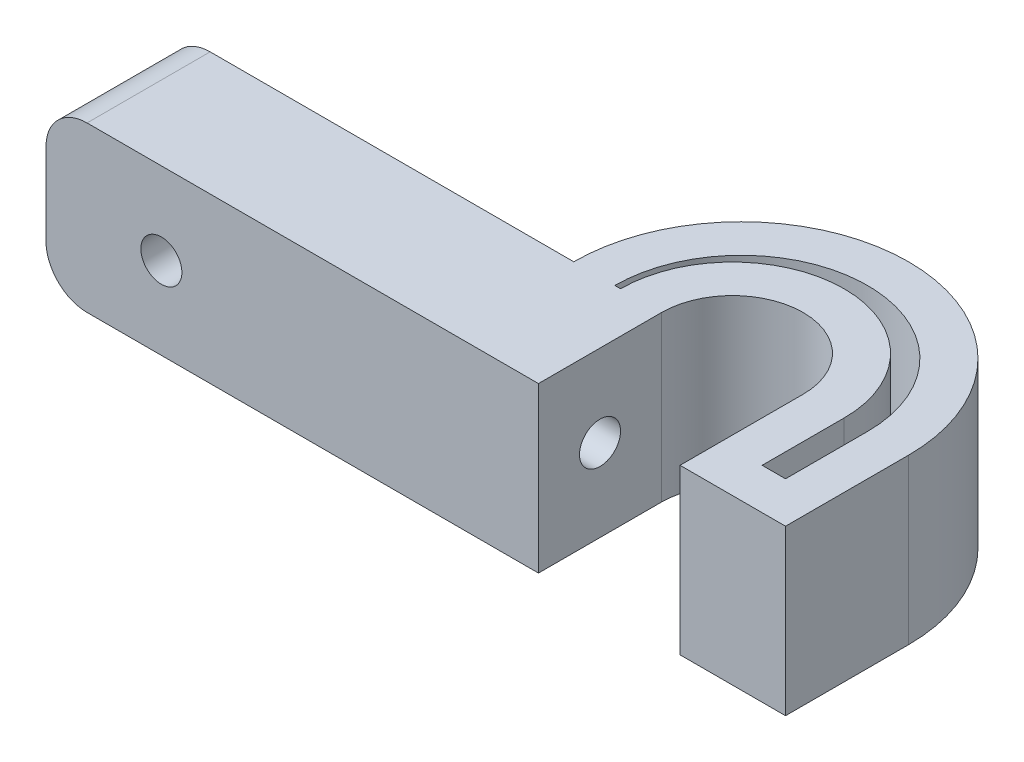
SolidWorks part; units mm, degrees
ref_plane "Plan de face" through (0, 0, 0) normal (0, 0, 1) x (1, 0, 0)
ref_plane "Plan de dessus" through (0, 0, 0) normal (0, 1, 0) x (1, 0, 0)
ref_plane "Plan de droite" through (0, 0, 0) normal (1, 0, 0) x (0, 0, -1)
sketch "Esquisse1" plane through (0, 0, 0) normal (0, 0, 1) x (1, 0, 0)
  line L1 (-50, -20) -> (60, -20)
  line L2 (-60, -10) -> (-60, 10)
  line L3 (-50, 20) -> (60, 20)
  line L4 (60, -20) -> (60, 20)
  line L5 (-60, -20) -> (60, 20) construction
  line L6 (-60, 20) -> (60, -20) construction
  arc A2 (-50, -20) -> (-60, -10) centre (-50, -10) cw
  arc A3 (-60, 10) -> (-50, 20) centre (-50, 10) cw
  point P0 (0, 0)
  dimension "D1" = 120
  dimension "D2" = 40
extrude "Boss.-Extru.1" add sketch "Esquisse1" along normal blind 30
sketch "Esquisse3" plane through (0, 0, 0) normal (0, 0, -1) x (-1, 0, 0)
  circle A0 centre (31.8868, 0) radius 5
  dimension "D1" = 10
extrude "Enlèv. mat.-Extru.1" cut sketch "Esquisse3" against normal blind 40
sketch "Esquisse4" plane through (60, 0, 0) normal (1, 0, 0) x (0, 0, -1)
  circle A0 centre (-15, 0) radius 5
extrude "Enlèv. mat.-Extru.2" cut sketch "Esquisse4" against normal blind 30
sketch "Esquisse5" plane through (0, 0, 0) normal (0, 0, -1) x (-1, 0, 0)
  line L0 (-60, -20) -> (-60, 20)
  line L4 (-60, 20) -> (50, 20) construction
  line L5 (-60, 20) -> (-34.2966, 20)
  line L6 (-60, -20) -> (-34.2966, -20)
  line L7 (50, -20) -> (-60, -20) construction
  arc A3 (-34.2966, -20) -> (-34.2966, 20) centre (-54.2966, 0) ccw
ref_plane "Plan1" through (0, 0, 0) normal (0, -1, 0) x (-1, 0, 0)
ref_plane "Plan4" through (0, 0, 30) normal (0, 0, 1) x (1, 0, 0)
sketch "Esquisse11" plane through (0, 0, 0) normal (0, -1, 0) x (-1, 0, 0)
  line L0 (-94.5006, -30) -> (-120.2006, -30)
  line L3 (-120.2006, 0) -> (-120.2006, -30)
  line L4 (-94.5006, -30) -> (-94.5006, 0)
  line L5 (-60, 0) -> (-34.2966, 0) construction
  arc A0 (-94.5006, 0) -> (-60, 0) centre (-77.2503, 0) cw
  arc A1 (-120.2006, 0) -> (-38.6041, 0) centre (-79.4023, 0) cw
  dimension "D1" = 25.7
extrude "Extru.-Mince1" add sketch "Esquisse11" along normal mid plane 40 thin
